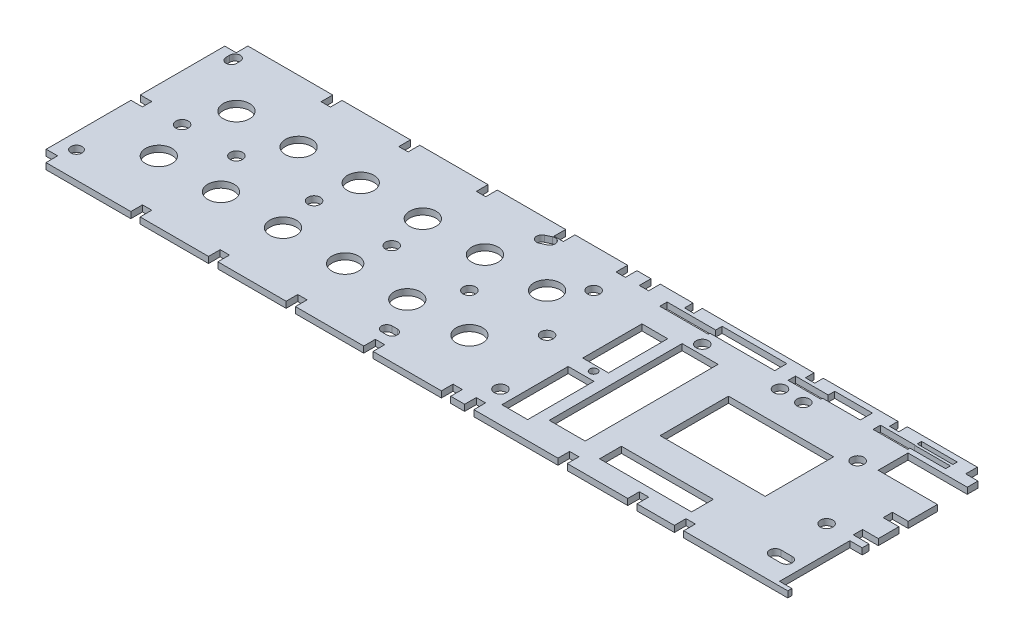
SolidWorks part; units mm, degrees
ref_plane "Front Plane" through (0, 0, 0) normal (0, 0, 1) x (1, 0, 0)
ref_plane "Top Plane" through (0, 0, 0) normal (0, 1, 0) x (1, 0, 0)
ref_plane "Right Plane" through (0, 0, 0) normal (1, 0, 0) x (0, 0, -1)
sketch "Sketch1" plane through (0, 0, 0) normal (0, 1, 0) x (1, 0, 0)
  line L0 (485, 0) -> (485, 130) construction
  line L1 (0, 130) -> (485, 130)
  line L2 (0, 130) -> (0, 0)
  line L3 (0, 0) -> (485, 0)
  line L4 (485, 130) -> (485, 0)
  line L5 (0, 130) -> (0, 0) construction
  line L6 (485, 130) -> (0, 130) construction
  line L7 (0, 0) -> (485, 0) construction
  line L8 (444.7316, 118.9355) -> (444.7316, 117.5)
  line L9 (485, 47.9413) -> (477.0415, 47.9413)
  line L10 (485, 47.9413) -> (485, 2.6445)
  line L11 (485, 2.6445) -> (477.0415, 2.6445)
  line L12 (477.0415, 47.9413) -> (477.0415, 2.6445)
  line L13 (485, 77.533) -> (474.8926, 77.533)
  line L14 (485, 77.533) -> (485, 71.533)
  line L15 (485, 71.533) -> (474.8926, 71.533)
  line L16 (474.8926, 77.533) -> (474.8926, 71.533)
  line L17 (485, 58.3069) -> (474.8926, 58.3069)
  line L18 (485, 58.3069) -> (485, 52.3069)
  line L19 (485, 52.3069) -> (474.8926, 52.3069)
  line L20 (474.8926, 58.3069) -> (474.8926, 52.3069)
  line L21 (485, 115.574) -> (446.8521, 115.574)
  line L22 (485, 115.574) -> (485, 96.3378)
  line L23 (485, 96.3378) -> (446.8521, 96.3378)
  line L24 (446.8521, 115.574) -> (446.8521, 96.3378)
  line L25 (444.7316, 126.4) -> (467.7258, 126.4)
  line L26 (444.7316, 126.4) -> (444.7316, 123.5923)
  line L27 (444.7316, 123.5923) -> (467.7258, 123.5923)
  line L28 (467.7258, 126.4) -> (467.7258, 123.5923)
  line L29 (467.6918, 122.0219) -> (444.7316, 122.0219)
  line L30 (467.6918, 122.0219) -> (467.6918, 118.9355)
  line L31 (467.6918, 118.9355) -> (444.7316, 118.9355)
  line L33 (425.9983, 130) -> (431.9983, 130)
  line L34 (425.9983, 130) -> (425.9983, 124.5)
  line L35 (425.9983, 124.5) -> (431.9983, 124.5)
  line L36 (431.9983, 130) -> (431.9983, 124.5)
  line L37 (422.448, 122.2354) -> (444.7316, 122.2354)
  line L38 (422.448, 122.2354) -> (422.448, 117.5)
  line L39 (422.448, 117.5) -> (444.7316, 117.5)
  line L40 (444.7316, 122.2354) -> (444.7316, 122.0219)
  line L41 (10.0347, 119.0046) -> (10.0347, 116.6922) construction
  line L42 (371.8879, 130) -> (377.8879, 130)
  line L43 (371.8879, 130) -> (371.8879, 124.5)
  line L44 (371.8879, 124.5) -> (377.8879, 124.5)
  line L45 (377.8879, 130) -> (377.8879, 124.5)
  line L46 (294.0008, 130) -> (300.0008, 130)
  line L47 (294.0008, 130) -> (294.0008, 124.5)
  line L48 (294.0008, 124.5) -> (300.0008, 124.5)
  line L49 (300.0008, 130) -> (300.0008, 124.5)
  line L50 (266.9165, 130) -> (272.9165, 130)
  line L51 (266.9165, 130) -> (266.9165, 122.5)
  line L52 (266.9165, 122.5) -> (272.9165, 122.5)
  line L53 (272.9165, 130) -> (272.9165, 122.5)
  line L54 (251.9112, 130) -> (257.9112, 130)
  line L55 (251.9112, 130) -> (251.9112, 122.5)
  line L56 (251.9112, 122.5) -> (257.9112, 122.5)
  line L57 (257.9112, 130) -> (257.9112, 122.5)
  line L58 (211.9807, 130) -> (217.9807, 130)
  line L59 (211.9807, 130) -> (211.9807, 122.5)
  line L60 (211.9807, 122.5) -> (217.9807, 122.5)
  line L61 (217.9807, 130) -> (217.9807, 122.5)
  line L62 (161.992, 130) -> (167.992, 130)
  line L63 (161.992, 130) -> (161.992, 122.5)
  line L64 (161.992, 122.5) -> (167.992, 122.5)
  line L65 (167.992, 130) -> (167.992, 122.5)
  line L66 (112.0325, 130) -> (118.0325, 130)
  line L67 (112.0325, 130) -> (112.0325, 122.5)
  line L68 (112.0325, 122.5) -> (118.0325, 122.5)
  line L69 (118.0325, 130) -> (118.0325, 122.5)
  line L70 (62.0027, 130) -> (68.0027, 130)
  line L71 (62.0027, 130) -> (62.0027, 122.5)
  line L72 (62.0027, 122.5) -> (68.0027, 122.5)
  line L73 (68.0027, 130) -> (68.0027, 122.5)
  line L74 (425.0315, 89.4923) -> (357.3425, 89.4923)
  line L75 (425.0315, 89.4923) -> (425.0315, 45.4306)
  line L76 (425.0315, 45.4306) -> (357.3425, 45.4306)
  line L77 (357.3425, 89.4923) -> (357.3425, 45.4306)
  line L78 (410.025, 27.0715) -> (350.7971, 27.0715)
  line L79 (410.025, 27.0715) -> (410.025, 13.0229)
  line L80 (410.025, 13.0229) -> (350.7971, 13.0229)
  line L81 (350.7971, 27.0715) -> (350.7971, 13.0229)
  line L82 (289.1745, 101.9445) -> (305.7775, 101.9445)
  line L83 (289.1745, 101.9445) -> (289.1745, 63.8011)
  line L84 (289.1745, 11.7457) -> (305.7775, 11.7457)
  line L85 (305.7775, 101.9445) -> (305.7775, 63.8011)
  line L86 (313.1211, 103.8603) -> (336.2695, 103.8603)
  line L87 (313.1211, 103.8603) -> (313.1211, 18.2911)
  line L88 (313.1211, 18.2911) -> (336.2695, 18.2911)
  line L89 (336.2695, 103.8603) -> (336.2695, 18.2911)
  line L90 (411.997, 0) -> (417.997, 0)
  line L91 (411.997, 0) -> (411.997, 7.5)
  line L92 (411.997, 7.5) -> (417.997, 7.5)
  line L93 (417.997, 0) -> (417.997, 7.5)
  line L94 (381.9632, 0) -> (387.9632, 0)
  line L95 (381.9632, 0) -> (381.9632, 7.5)
  line L96 (381.9632, 7.5) -> (387.9632, 7.5)
  line L97 (387.9632, 0) -> (387.9632, 7.5)
  line L98 (337.0209, 0) -> (343.0209, 0)
  line L99 (337.0209, 0) -> (337.0209, 7.5)
  line L100 (337.0209, 7.5) -> (343.0209, 7.5)
  line L101 (343.0209, 0) -> (343.0209, 7.5)
  line L102 (261.9696, 0) -> (267.9696, 0)
  line L103 (261.9696, 0) -> (261.9696, 7.5)
  line L104 (261.9696, 7.5) -> (267.9696, 7.5)
  line L105 (267.9696, 0) -> (267.9696, 7.5)
  line L106 (276.9208, 0) -> (282.9208, 0)
  line L107 (276.9208, 0) -> (276.9208, 7.5)
  line L108 (276.9208, 7.5) -> (282.9208, 7.5)
  line L109 (282.9208, 0) -> (282.9208, 7.5)
  line L110 (211.9807, 0) -> (217.9807, 0)
  line L111 (211.9807, 0) -> (211.9807, 7.5)
  line L112 (211.9807, 7.5) -> (217.9807, 7.5)
  line L113 (217.9807, 0) -> (217.9807, 7.5)
  line L114 (161.992, 0) -> (167.992, 0)
  line L115 (161.992, 0) -> (161.992, 7.5)
  line L116 (161.992, 7.5) -> (167.992, 7.5)
  line L117 (167.992, 0) -> (167.992, 7.5)
  line L118 (112.0325, 0) -> (118.0325, 0)
  line L119 (112.0325, 0) -> (112.0325, 7.5)
  line L120 (112.0325, 7.5) -> (118.0325, 7.5)
  line L121 (118.0325, 0) -> (118.0325, 7.5)
  line L122 (62.0027, 0) -> (68.0027, 0)
  line L123 (62.0027, 0) -> (62.0027, 7.5)
  line L124 (62.0027, 7.5) -> (68.0027, 7.5)
  line L125 (68.0027, 0) -> (68.0027, 7.5)
  line L126 (0, 130) -> (7.3855, 130)
  line L127 (0, 130) -> (0, 122.5)
  line L128 (0, 122.5) -> (7.3855, 122.5)
  line L129 (7.3855, 130) -> (7.3855, 122.5)
  line L130 (0, 0) -> (7.3855, 0)
  line L131 (0, 0) -> (0, 7.5)
  line L132 (0, 7.5) -> (7.3855, 7.5)
  line L133 (7.3855, 0) -> (7.3855, 7.5)
  line L134 (485, 130) -> (477.0415, 130)
  line L135 (485, 130) -> (485, 122.492)
  line L136 (485, 122.492) -> (477.0415, 122.492)
  line L137 (477.0415, 130) -> (477.0415, 122.492)
  line L138 (0, 68.0866) -> (7.3855, 68.0866)
  line L139 (0, 68.0866) -> (0, 62.0866)
  line L140 (0, 62.0866) -> (7.3855, 62.0866)
  line L141 (7.3855, 68.0866) -> (7.3855, 62.0866)
  line L142 (13.4263, 119.0046) -> (13.4263, 116.6922)
  line L143 (6.6431, 119.0046) -> (6.6431, 116.6922)
  line L144 (209.8069, 16.987) -> (213.2636, 16.987) construction
  line L145 (209.8069, 20.3348) -> (213.2636, 20.3348)
  line L146 (209.8069, 13.6392) -> (213.2636, 13.6392)
  line L147 (213.2636, 118.5927) -> (209.7734, 116.9365) construction
  line L148 (214.7266, 115.5098) -> (211.2364, 113.8536)
  line L149 (211.8006, 121.6756) -> (208.3104, 120.0194)
  line L150 (460, 16.987) -> (467.2539, 16.987) construction
  line L151 (460, 20.6206) -> (467.2539, 20.6206)
  line L152 (460, 13.3534) -> (467.2539, 13.3534)
  line L153 (289.1745, 54.4287) -> (289.1745, 11.7457)
  line L154 (285.0858, 122.2354) -> (316.3348, 122.2354)
  line L155 (285.0858, 122.2354) -> (285.0858, 117.5)
  line L156 (285.0858, 117.5) -> (316.3348, 117.5)
  line L157 (316.3348, 118.5927) -> (316.3348, 117.5)
  line L158 (367.7301, 122.2354) -> (388.8323, 122.2354)
  line L159 (367.7301, 122.2354) -> (367.7301, 117.5)
  line L160 (367.7301, 117.5) -> (388.8323, 117.5)
  line L161 (388.8323, 118.5927) -> (388.8323, 117.5)
  line L162 (358.0245, 126.4) -> (316.3348, 126.4)
  line L163 (358.0245, 126.4) -> (358.0245, 118.5927)
  line L164 (358.0245, 118.5927) -> (316.3348, 118.5927)
  line L165 (316.3348, 126.4) -> (316.3348, 122.2354)
  line L166 (413.0962, 126.4) -> (388.8323, 126.4)
  line L167 (413.0962, 126.4) -> (413.0962, 118.5927)
  line L168 (413.0962, 118.5927) -> (388.8323, 118.5927)
  line L169 (388.8323, 126.4) -> (388.8323, 122.2354)
  line L170 (305.7775, 63.8011) -> (289.1745, 63.8011)
  line L172 (305.7775, 54.4287) -> (289.1745, 54.4287)
  line L174 (305.7775, 54.4287) -> (305.7775, 11.7457)
  circle A0 centre (40.0138, 90.005) radius 8.5
  circle A1 centre (65, 65) radius 4
  circle A2 centre (80.0138, 90.005) radius 8.5
  circle A3 centre (120.0138, 90.005) radius 8.5
  circle A4 centre (160.0138, 90.005) radius 8.5
  circle A5 centre (200.0138, 90.005) radius 8.5
  circle A6 centre (240.0138, 90.005) radius 8.5
  circle A7 centre (80.0138, 40.005) radius 8.5
  circle A8 centre (120.0138, 40.005) radius 8.5
  circle A9 centre (160.0138, 40.005) radius 8.5
  circle A10 centre (200.0138, 40.005) radius 8.5
  circle A11 centre (240.0138, 40.005) radius 8.5
  circle A12 centre (40.0138, 40.005) radius 8.5
  circle A13 centre (30, 65) radius 4
  circle A14 centre (115, 65) radius 4
  circle A15 centre (165, 65) radius 4
  circle A16 centre (215, 65) radius 4
  circle A17 centre (265, 65) radius 4
  circle A18 centre (255, 105) radius 4
  circle A19 centre (280, 20) radius 4
  circle A20 centre (320, 110) radius 4
  circle A21 centre (460, 50) radius 4
  circle A22 centre (435, 95) radius 4
  circle A23 centre (370, 110) radius 4
  circle A24 centre (385, 110) radius 4
  arc A25 (13.4263, 119.0046) -> (6.6431, 119.0046) centre (10.0347, 119.0046) ccw
  arc A26 (6.6431, 116.6922) -> (13.4263, 116.6922) centre (10.0347, 116.6922) ccw
  circle A27 centre (10.0347, 16.987) radius 3.6258
  arc A28 (209.8069, 20.3348) -> (209.8069, 13.6392) centre (209.8069, 16.987) ccw
  arc A29 (213.2636, 13.6392) -> (213.2636, 20.3348) centre (213.2636, 16.987) ccw
  arc A30 (214.7266, 115.5098) -> (211.8006, 121.6756) centre (213.2636, 118.5927) ccw
  arc A31 (208.3104, 120.0194) -> (211.2364, 113.8536) centre (209.7734, 116.9365) ccw
  arc A32 (460, 20.6206) -> (460, 13.3534) centre (460, 16.987) ccw
  arc A33 (467.2539, 13.3534) -> (467.2539, 20.6206) centre (467.2539, 16.987) ccw
  circle A34 centre (300, 60) radius 2.467
  point P202 (10.0347, 117.8484)
  point P207 (211.5352, 16.987)
  point P216 (211.5185, 117.7646)
  point P223 (463.6269, 16.987)
  dimension "D23" = 17
  dimension "D24" = 8
  dimension "D1" = 6
  dimension "D2" = 6
  dimension "D3" = 6
  dimension "D4" = 6
  dimension "D5" = 6
  dimension "D6" = 6
  dimension "D7" = 6
  dimension "D8" = 6
  dimension "D9" = 6
  dimension "D10" = 7.5
  dimension "D11" = 5.5
  dimension "D12" = 6
  dimension "D13" = 6
  dimension "D14" = 6
  dimension "D15" = 6
  dimension "D16" = 6
  dimension "D17" = 6
  dimension "D18" = 6
  dimension "D19" = 7.5
  dimension "D22" = 6
  dimension "D26" = 12.5
  dimension "D27" = 3.6
  dimension "D20" = 6
  dimension "D21" = 2
  dimension "D25" = 5
extrude "Boss-Extrude1" add sketch "Sketch1" against normal blind 4 contours L138 L141 L140 L2 L132 L133 L3 L123 L124 L125 L119 L120 L121 L115 L116 L117 L111 L112 L113 L103 L104 L105 L107 L108 L109 L99 L100 L101 L95 L96 L97 L91 L92 L93 L4 L11 L12 L9 L19 L20 L17
